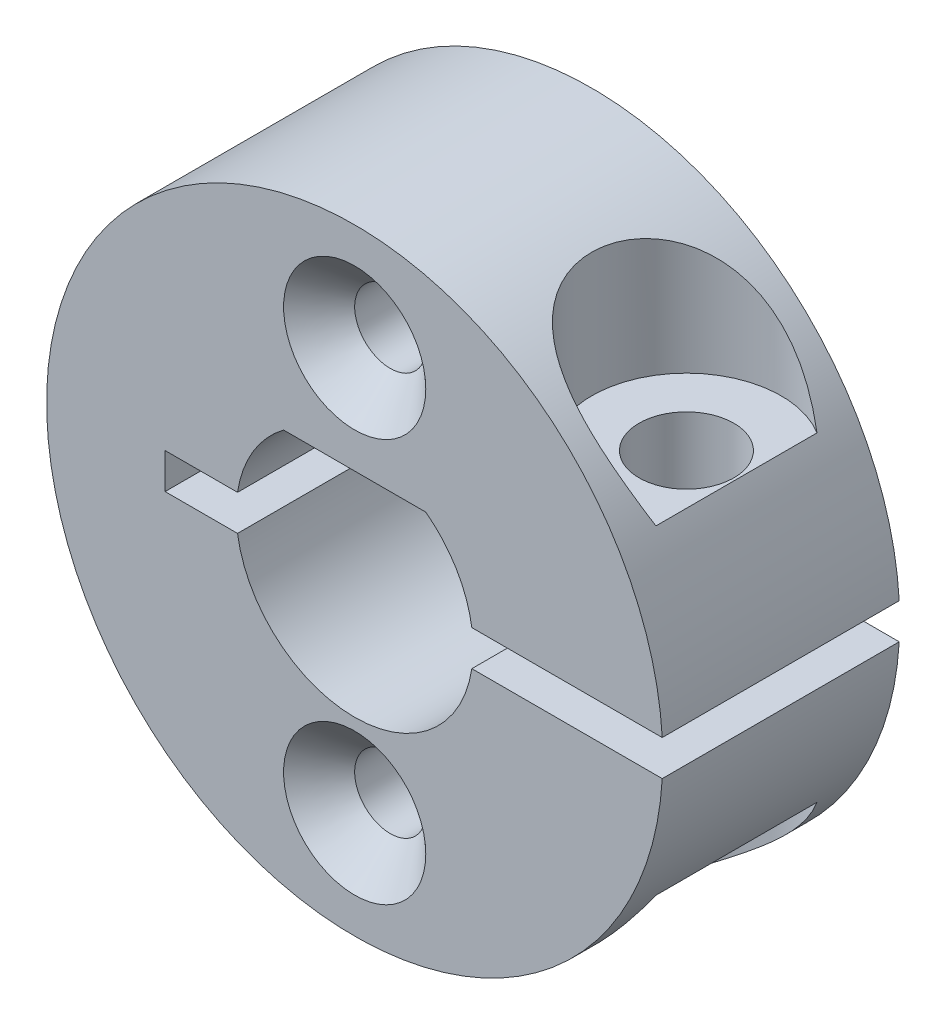
SolidWorks part; units mm, degrees
material "1060 合金"
ref_plane "前视基准面" through (0, 0, 0) normal (0, 0, 1) x (1, 0, 0)
ref_plane "上视基准面" through (0, 0, 0) normal (0, 1, 0) x (1, 0, 0)
ref_plane "右视基准面" through (0, 0, 0) normal (1, 0, 0) x (0, 0, -1)
sketch "草图1" plane through (0, 0, 0) normal (0, 0, 1) x (1, 0, 0)
  line L0 (-3, 4) -> (3, 4)
  arc A0 (-3, 4) -> (3, 4) centre (0, 0) ccw
  circle A1 centre (0, 0) radius 13
  circle A2 centre (0, 0) radius 8.5 construction
  circle A3 centre (0, 8.5) radius 1.5
  circle A5 centre (0, -8.5) radius 1.5
  dimension "D1" = 10
  dimension "D2" = 26
  dimension "D3" = 17
  dimension "D4" = 3
  dimension "D5" = 4
  dimension "D6" = 3
extrude "凸台-拉伸1" add sketch "草图1" along normal blind 10
sketch "草图2" plane through (0, 0, 0) normal (0, 1, 0) x (1, 0, 0)
  line L0 (13, 0) -> (-13, 0) construction
  circle A0 centre (9, -5) radius 2
  dimension "D1" = 4
  dimension "D2" = 9
  dimension "D3" = 5
extrude "切除-拉伸1" cut sketch "草图2" against normal through all and the other way through all
sketch "草图3" plane through (0, 0, 10) normal (0, 0, 1) x (1, 0, 0)
  line L0 (-8, 0.75) -> (-8, -0.75)
  line L1 (-14.4698, 0.75) -> (14.4698, 0.75)
  line L2 (-14.4698, 0.75) -> (-14.4698, -0.75)
  line L3 (-14.4698, -0.75) -> (14.4698, -0.75)
  line L4 (14.4698, 0.75) -> (14.4698, -0.75)
  line L5 (-14.4698, 0.75) -> (14.4698, -0.75) construction
  line L6 (-14.4698, -0.75) -> (14.4698, 0.75) construction
  point P0 (0, 0)
  circle M3 centre (0, 0) radius 13
  arc M4 (3, 4) -> (-3, 4) centre (0, 0) cw
  dimension "D1" = 1.5
  dimension "D2" = 8
extrude "切除-拉伸2" cut sketch "草图3" against normal blind 10 contours L3 L1 M4 | L0 L3 L1 M4 | L3 L1 M4 M3 | L4 L1 L3 M3
chamfer "倒角1" distance 1.5 angle 45 2 edges at (1.5, -8.5, 10) (1.5, 8.5, 10)
ref_plane "基准面2" through (0, 9.75, 0) normal (0, -1, 0) x (-1, 0, 0)
sketch "草图4" plane through (0, 9.75, 0) normal (0, -1, 0) x (-1, 0, 0)
  circle A0 centre (-9, -5) radius 4
  dimension "D1" = 8
extrude "切除-拉伸6" cut sketch "草图4" against normal through all and the other way blind 3
mirror "镜向1" about plane through (0, 0, 0) normal (0, 1, 0) of "切除-拉伸6"
